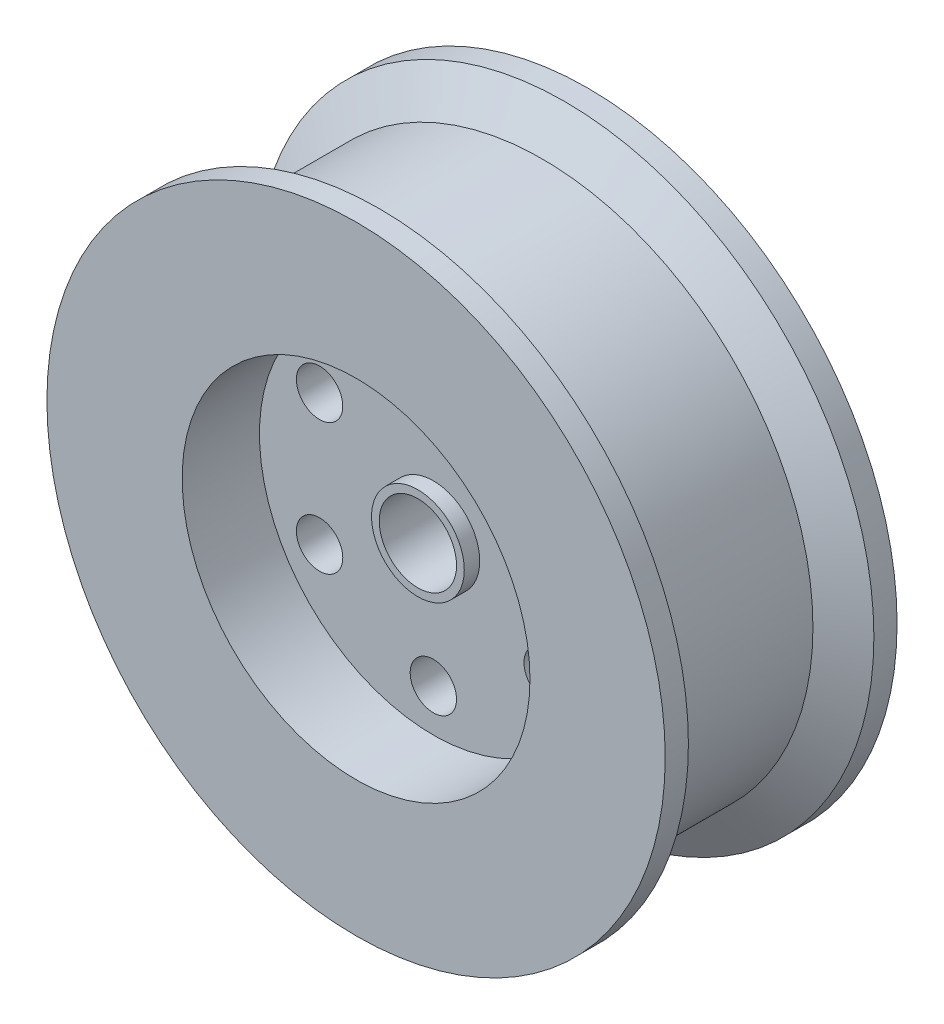
SolidWorks part; units mm, degrees
material "6061-T6 (SS)"
ref_plane "Front Plane" through (0, 0, 0) normal (0, 0, 1) x (1, 0, 0)
ref_plane "Top Plane" through (0, 0, 0) normal (0, 1, 0) x (1, 0, 0)
ref_plane "Right Plane" through (0, 0, 0) normal (1, 0, 0) x (0, 0, -1)
sketch "Sketch1" plane through (0, 0, 0) normal (0, 0, 1) x (1, 0, 0)
  circle A0 centre (0, 0) radius 40
  circle A1 centre (0, 0) radius 5
  dimension "D1" = 10
  dimension "D2" = 80
extrude "Boss-Extrude1" add sketch "Sketch1" along normal mid plane 30
sketch "Sketch2" plane through (0, 0, 15) normal (0, 0, 1) x (1, 0, 0)
  circle A0 centre (0, 0) radius 22.5
  circle A1 centre (0, 0) radius 40 construction
  dimension "D1" = 17.5
extrude "Cut-Extrude2" cut sketch "Sketch2" against normal blind 10
mirror "Mirror2" about plane through (0, 0, 0) normal (0, 0, 1) of "Cut-Extrude2"
sketch "Sketch3" plane through (0, 0, 5) normal (0, 0, 1) x (1, 0, 0)
  line L0 (0, -1000) -> (0, 49000) construction
  circle A0 centre (0, 17) radius 3
  dimension "D2" = 6
  dimension "D1" = 17
extrude "Cut-Extrude8" cut sketch "Sketch3" against normal blind 10
pattern_circular "CirPattern1" count 6 over 360 about axis through (0, 0, 0) along (0, 0, 1) of "Cut-Extrude8"
sketch "Sketch4" plane through (0, 0, 5) normal (0, 0, 1) x (1, 0, 0)
  circle A0 centre (0, 0) radius 6
  circle A1 centre (0, 0) radius 5 construction
  circle A2 centre (0, 0) radius 5
  dimension "D1" = 12
extrude "Boss-Extrude3" add sketch "Sketch4" along normal blind 2 and the other way blind 7 contours A0 | A2
sketch "Sketch5" plane through (0, 0, 0) normal (0, 1, 0) x (1, 0, 0)
  line L0 (0, 0) -> (0, 21.4107) construction
  line L1 (40, 12) -> (35, 9.1132)
  line L2 (40, -15) -> (40, 15) construction
  line L3 (35, 9.1132) -> (35, -9.1132)
  line L4 (35, -9.1132) -> (40, -12)
  line L5 (40, -12) -> (40, 12)
  line L7 (40, 15) -> (-40, 15) construction
  line L8 (-40, -15) -> (40, -15) construction
  dimension "D1" = 5
  dimension "D2" = 3
  dimension "D3" = 3
  dimension "D4" = 60
  dimension "D5" = 60
revolve "Cut-Revolve2" cut sketch "Sketch5" angle 360 about L0
